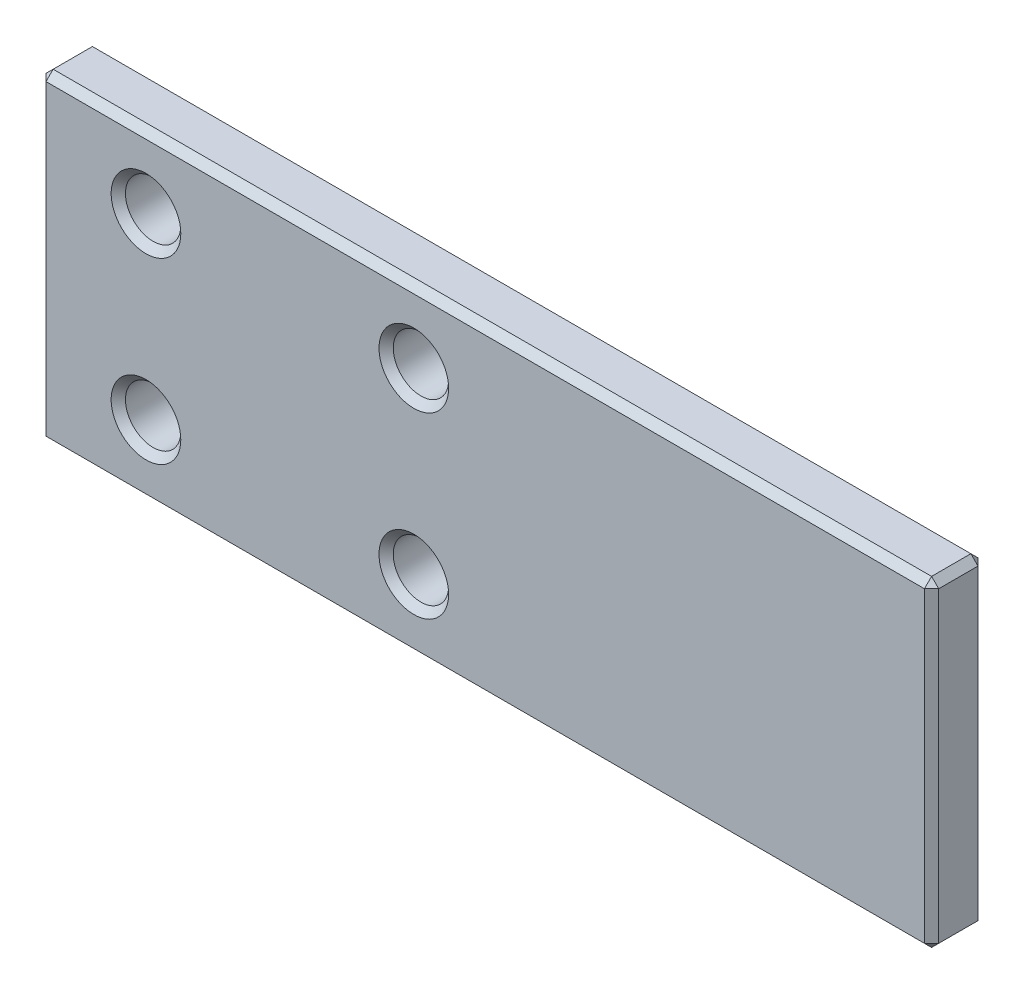
SolidWorks part; units mm, degrees
material "Aluminiumoxid"
ref_plane "Ebene vorne" through (0, 0, 0) normal (0, 0, 1) x (1, 0, 0)
ref_plane "Ebene oben" through (0, 0, 0) normal (0, 1, 0) x (1, 0, 0)
ref_plane "Ebene rechts" through (0, 0, 0) normal (1, 0, 0) x (0, 0, -1)
sketch "Skizze1" plane through (0, 0, 0) normal (0, 0, 1) x (1, 0, 0)
  line L1 (-15.3775, 8.4407) -> (34.6225, 8.4407)
  line L2 (-15.3775, 8.4407) -> (-15.3775, -9.5593)
  line L3 (-15.3775, -9.5593) -> (34.6225, -9.5593)
  line L4 (34.6225, 8.4407) -> (34.6225, -9.5593)
  dimension "D1" = 18
  dimension "D2" = 50
extrude "Aufsatz-Linear austragen1" add sketch "Skizze1" along normal blind 3
sketch "Skizze2" plane through (0, 0, 0) normal (0, 0, -1) x (-1, 0, 0)
  line L0 (-34.6225, 8.4407) -> (15.3775, 8.4407) construction
  line L1 (15.3775, 8.4407) -> (15.3775, -9.5593) construction
  line L2 (-34.6225, -0.5593) -> (15.3775, -0.5593) construction
  line L3 (-34.6225, -9.5593) -> (-34.6225, 8.4407) construction
  line L4 (2.3775, -9.5593) -> (2.3775, 8.4407) construction
  line L5 (15.3775, -9.5593) -> (-34.6225, -9.5593) construction
  circle A0 centre (9.3775, 4.4407) radius 1.55
  circle A1 centre (-5.6225, 4.4407) radius 1.55
  circle A2 centre (-5.6225, -5.5593) radius 1.55
  circle A3 centre (9.3775, -5.5593) radius 1.55
  dimension "D1" = 3.1
  dimension "D2" = 4
  dimension "D3" = 6
  dimension "D4" = 13
  dimension "D5" = 2
  dimension "D6" = 2
extrude "Schnitt-Linear austragen1" cut sketch "Skizze2" against normal through all
chamfer "Fase1" distance 0.4 angle 45 20 edges at (-10.9275, -5.5593, 3) (-10.9275, -5.5593, 0) (4.0725, -5.5593, 3) (4.0725, -5.5593, 0) (4.0725, 4.4407, 3) (4.0725, 4.4407, 0) (-10.9275, 4.4407, 0) (-10.9275, 4.4407, 3) (-15.3775, -0.5593, 0) (9.6225, -9.5593, 0) (34.6225, -0.5593, 0) (9.6225, 8.4407, 0) (-15.3775, -0.5593, 3) (-15.3775, 8.4407, 1.5) (9.6225, 8.4407, 3) (34.6225, 8.4407, 1.5) (34.6225, -0.5593, 3) (34.6225, -9.5593, 1.5) (9.6225, -9.5593, 3) (-15.3775, -9.5593, 1.5)
